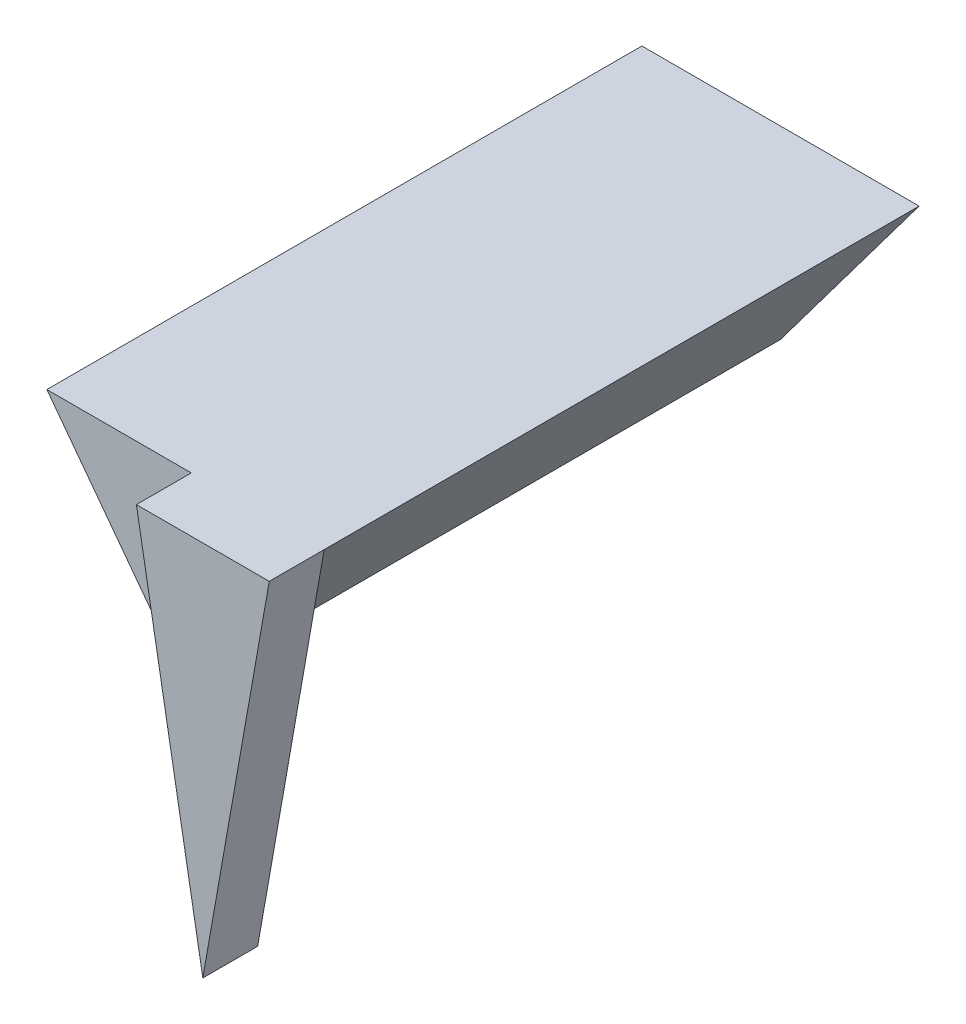
SolidWorks part; units mm, degrees
ref_plane "Front Plane" through (0, 0, 0) normal (0, 0, 1) x (1, 0, 0)
ref_plane "Top Plane" through (0, 0, 0) normal (0, 1, 0) x (1, 0, 0)
ref_plane "Right Plane" through (0, 0, 0) normal (1, 0, 0) x (0, 0, -1)
sketch "Sketch1" plane through (0, 0, 0) normal (0, 0, 1) x (1, 0, 0)
  line L0 (0, 0) -> (-11.5, 65.2197)
  line L1 (-11.5, 65.2197) -> (11.5, 65.2197)
  line L2 (11.5, 65.2197) -> (0, 0)
  dimension "D1" = 23
  dimension "D2" = 20
extrude "Boss-Extrude1" add sketch "Sketch1" against normal blind 9.5
sketch "Sketch2" plane through (0, 0, -9.5) normal (0, 0, -1) x (-1, 0, 0)
  line L0 (-11.5, 65.2197) -> (36.5, 65.2197)
  line L1 (36.5, 65.2197) -> (12.5, 33.2197)
  line L2 (12.5, 33.2197) -> (-11.5, 65.2197)
  dimension "D1" = 40
  dimension "D2" = 48
extrude "Boss-Extrude2" add sketch "Sketch2" along normal blind 103
